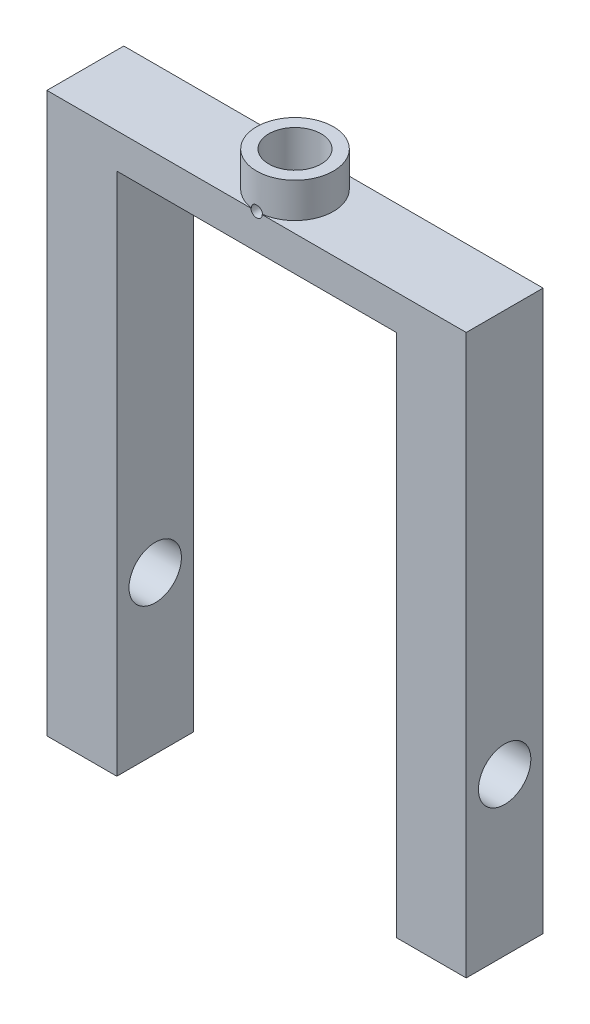
SolidWorks part; units mm, degrees
ref_plane "Front Plane" through (0, 0, 0) normal (0, 0, 1) x (1, 0, 0)
ref_plane "Top Plane" through (0, 0, 0) normal (0, 1, 0) x (1, 0, 0)
ref_plane "Right Plane" through (0, 0, 0) normal (1, 0, 0) x (0, 0, -1)
sketch "Sketch1" plane through (0, 0, 0) normal (0, 1, 0) x (1, 0, 0)
  circle A0 centre (0, 0) radius 6.985
  dimension "D1" = 13.97
extrude "Boss-Extrude1" add sketch "Sketch1" against normal blind 6.35
sketch "Sketch3" plane through (0, 0, 0) normal (0, 1, 0) x (1, 0, 0)
  circle A0 centre (0, 0) radius 4.7625
  circle A1 centre (0, 0) radius 6.985 construction
  dimension "D1" = 9.525
extrude "Cut-Extrude1" cut sketch "Sketch3" against normal blind 63.5
sketch "Sketch5" plane through (0, -6.35, 0) normal (0, -1, 0) x (-1, 0, 0)
  line L1 (38.1, -6.985) -> (-38.1, -6.985)
  line L2 (38.1, -6.985) -> (38.1, 6.985)
  line L3 (38.1, 6.985) -> (-38.1, 6.985)
  line L4 (-38.1, -6.985) -> (-38.1, 6.985)
  line L5 (38.1, -6.985) -> (-38.1, 6.985) construction
  line L6 (38.1, 6.985) -> (-38.1, -6.985) construction
  circle A0 centre (0, 0) radius 4.7625 construction
  point P0 (0, 0)
  dimension "D1" = 76.2
  dimension "D2" = 13.97
extrude "Boss-Extrude2" add sketch "Sketch5" along normal blind 101.6
sketch "Sketch6" plane through (0, 0, -6.985) normal (0, 0, -1) x (-1, 0, 0)
  line L0 (0, -6.35) -> (-38.1, -6.35) construction
  line L1 (25.4, -12.7) -> (-25.4, -12.7)
  line L2 (25.4, -12.7) -> (25.4, -107.95)
  line L3 (25.4, -107.95) -> (-25.4, -107.95)
  line L4 (-25.4, -12.7) -> (-25.4, -107.95)
  line L5 (25.4, -12.7) -> (-25.4, -107.95) construction
  line L6 (25.4, -107.95) -> (-25.4, -12.7) construction
  line L7 (38.1, -107.95) -> (38.1, -6.35) construction
  line L8 (38.1, -107.95) -> (-38.1, -107.95) construction
  point P0 (0, -64.4831)
  point P14 (0, -60.325)
  dimension "D1" = 50.8
  dimension "D3" = 6.35
  dimension "D4" = 38.1
extrude "Cut-Extrude2" cut sketch "Sketch6" against normal through all
sketch "Sketch7" plane through (0, 0, 0) normal (0, 1, 0) x (1, 0, 0)
  circle A0 centre (0, 0) radius 4.7625
  dimension "D1" = 9.525
extrude "Cut-Extrude3" cut sketch "Sketch7" against normal through all
sketch "Sketch8" plane through (25.4, 0, 0) normal (-1, 0, 0) x (0, 0, 1)
  line L0 (6.985, -12.7) -> (-6.985, -12.7) construction
  line L1 (-6.985, -12.7) -> (-6.985, -107.95) construction
  circle A0 centre (0, -79.375) radius 4.7625
  dimension "D1" = 9.525
  dimension "D2" = 66.675
  dimension "D3" = 6.985
extrude "Cut-Extrude4" cut sketch "Sketch8" against normal blind 19.05 and the other way through all
sketch "Sketch9" plane through (0, 0, 6.985) normal (0, 0, 1) x (1, 0, 0)
  circle A0 centre (0, -6.35) radius 1.016
  dimension "D1" = 2.032
extrude "Cut-Extrude5" cut sketch "Sketch9" against normal up to surface (13.97 mm away)
